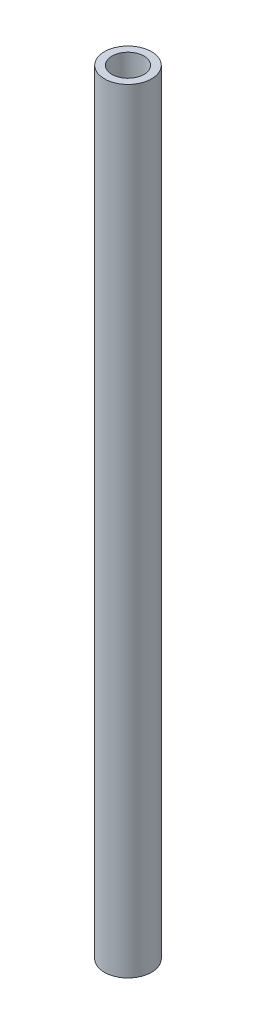
SolidWorks part; units mm, degrees
ref_plane "Front Plane" through (0, 0, 0) normal (0, 0, 1) x (1, 0, 0)
ref_plane "Top Plane" through (0, 0, 0) normal (0, 1, 0) x (1, 0, 0)
ref_plane "Right Plane" through (0, 0, 0) normal (1, 0, 0) x (0, 0, -1)
sketch "Sketch1" plane through (0, 0, 0) normal (0, 1, 0) x (1, 0, 0)
  circle A0 centre (0, 0) radius 9.5
  circle A1 centre (0, 0) radius 14
  dimension "D1" = 19
  dimension "D2" = 28
extrude "Boss-Extrude1" add sketch "Sketch1" along normal blind 460
